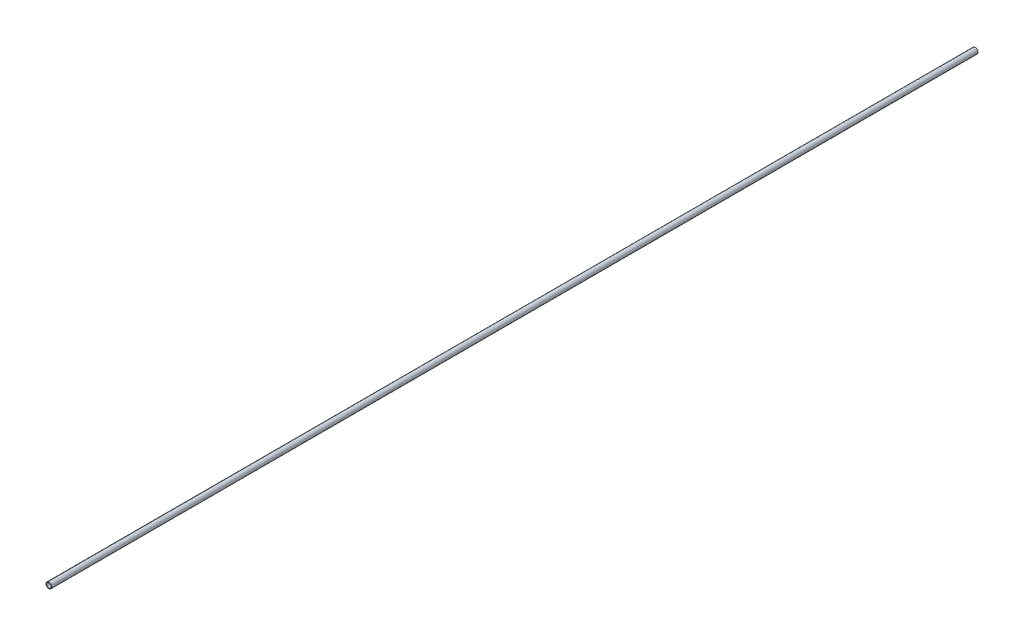
SolidWorks part; units mm, degrees
ref_plane "Front" through (0, 0, 0) normal (0, 0, 1) x (1, 0, 0)
ref_plane "Top" through (0, 0, 0) normal (0, 1, 0) x (1, 0, 0)
ref_plane "Side" through (0, 0, 0) normal (1, 0, 0) x (0, 0, -1)
other "Configuration Table"
sketch "PipeSketch" plane through (0, 0, 0) normal (0, 0, 1) x (1, 0, 0)
  circle A0 centre (0, 0) radius 16.764
  circle A1 centre (0, 0) radius 13.3858
  dimension "OuterDiameter" = 33.528
  dimension "InnerDiameter" = 26.7716
extrude "Extrusion" add sketch "PipeSketch" along normal blind 5486.4
sketch "FilterSketch" plane through (0, 0, 0) normal (0, 0, 1) x (1, 0, 0)
  circle A0 centre (0, 0) radius 12.7 construction
  dimension "NominalDiameter" = 25.4
